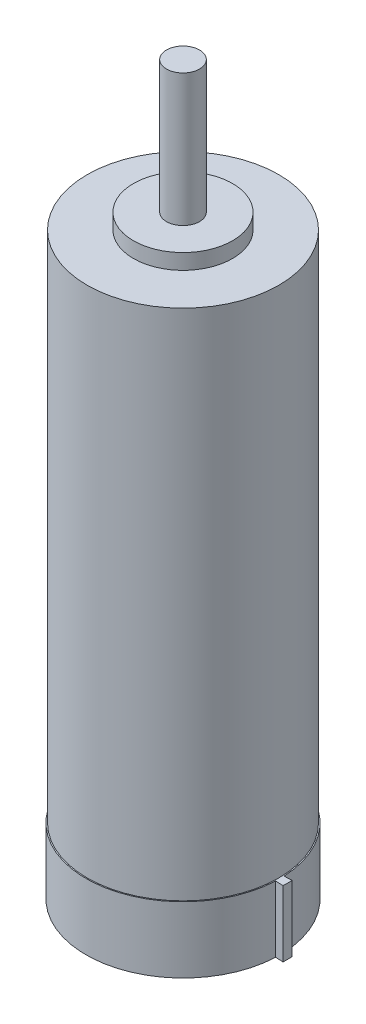
SolidWorks part; units mm, degrees
ref_plane "前视基准面" through (0, 0, 0) normal (0, 0, 1) x (1, 0, 0)
ref_plane "上视基准面" through (0, 0, 0) normal (0, 1, 0) x (1, 0, 0)
ref_plane "右视基准面" through (0, 0, 0) normal (1, 0, 0) x (0, 0, -1)
sketch "草图1" plane through (0, 0, 0) normal (0, 1, 0) x (1, 0, 0)
  line L3 (-9.799, 0) -> (0.2597, 0) construction
  line L4 (0, 0) -> (0, 5.7388) construction
  circle A0 centre (0, 0) radius 8.8
  dimension "D1" = 17.6
extrude "凸台-拉伸1" add sketch "草图1" along normal blind 6
sketch "草图6" plane through (0, 0, 0) normal (0, 0, 1) x (1, 0, 0)
  line L0 (8.8, 6) -> (-8.8, 6) construction
  line L1 (-8.8, 6) -> (-9.5, 6)
  line L2 (-8.8, 6) -> (-8.8, 0)
  line L3 (-8.8, 0) -> (-9.5, 0)
  line L4 (-9.5, 6) -> (-9.5, 0)
  line L5 (-8.8, 0) -> (8.8, 0) construction
  line L6 (-8.8, 6) -> (-8.8, 0) construction
  line L7 (0, 1.1836) -> (0, 0) construction
  dimension "D1" = 0.7
revolve "旋转1" add sketch "草图6" angle 5 mid plane about L7
pattern_circular "阵列(圆周)5" count 2 over 360 about axis through (0, 0, 0) along (0, 1, 0) of "旋转1"
sketch "草图7" plane through (0, 6, 0) normal (0, 1, 0) x (1, 0, 0)
  circle A0 centre (0, 0) radius 8.7
  dimension "D1" = 17.4
extrude "凸台-拉伸10" add sketch "草图7" along normal blind 46.6
sketch "草图8" plane through (0, 52.6, 0) normal (0, 1, 0) x (1, 0, 0)
  circle A0 centre (0, 0) radius 4.5
  dimension "D1" = 9
extrude "凸台-拉伸11" add sketch "草图8" along normal blind 1.4
sketch "草图9" plane through (0, 54, 0) normal (0, 1, 0) x (1, 0, 0)
  circle A0 centre (0, 0) radius 1.5
  dimension "D1" = 3
extrude "凸台-拉伸12" add sketch "草图9" along normal blind 12
sketch "草图10" plane through (0, 0, 0) normal (0, -1, 0) x (-1, 0, 0)
  line L0 (0, 0) -> (11.4472, 0) construction
  line L1 (0, 0) -> (0, -5.9162) construction
  point P1 (-6.72, 0)
  point P7 (6.72, 0)
  dimension "D1" = 13.44
hole_wizard "Ø2.0mm 暗销孔1" positions "3D草图2" profile "草图13" hole size "Ø2.0" standard "GB"
sketch3d "3D草图2"
  line L0 (0, 0, 0) -> (-11.4472, 0, 0) construction
  point P0 (-6.72, 0, 0)
sketch "草图13" plane through (-6.72, 0, 0) normal (1, 0, 0) x (0, 0, -1)
  line L0 (0, 0) -> (0, 5.6009)
  line L1 (0, 5.6009) -> (1, 5)
  line L2 (1, 5) -> (1, 0)
  line L5 (1, 0) -> (0, 0)
  line L10 (0, 5.6009) -> (-1, 5) construction
  line L11 (0, -6.35) -> (0, 107.95) construction
  dimension "孔直径" = 2
  dimension "孔深度" = 5
  dimension "导头角度" = 118
hole_wizard "Ø2.0mm 暗销孔2" positions "3D草图3" profile "草图15" hole size "Ø2.0" standard "GB"
sketch3d "3D草图3"
  point P0 (6.72, 0, 0)
sketch "草图15" plane through (6.72, 0, 0) normal (1, 0, 0) x (0, 0, -1)
  line L0 (0, 0) -> (0, 5.6009)
  line L1 (0, 5.6009) -> (1, 5)
  line L2 (1, 5) -> (1, 0)
  line L5 (1, 0) -> (0, 0)
  line L10 (0, 5.6009) -> (-1, 5) construction
  line L11 (0, -6.35) -> (0, 107.95) construction
  dimension "孔直径" = 2
  dimension "孔深度" = 5
  dimension "导头角度" = 118
